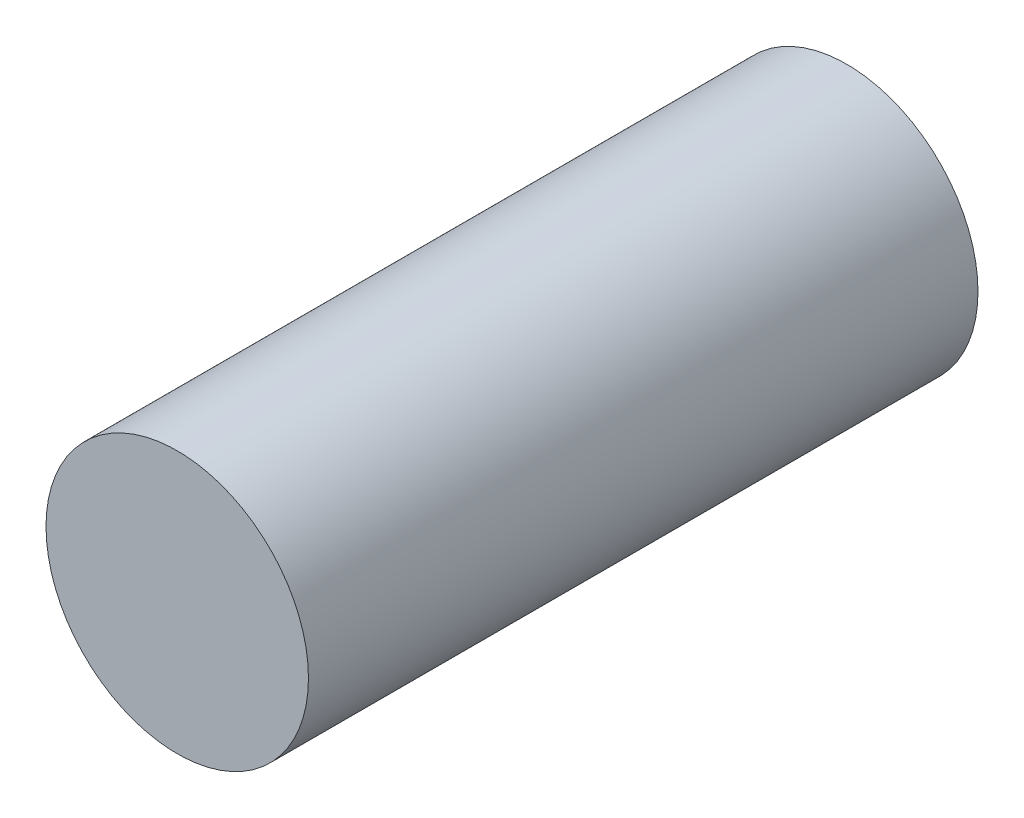
SolidWorks part; units mm, degrees
material "Delrin 2700 NC010, Low Viscosity Acetal Copolymer (SS)"
ref_plane "Front Plane" through (0, 0, 0) normal (0, 0, 1) x (1, 0, 0)
ref_plane "Top Plane" through (0, 0, 0) normal (0, 1, 0) x (1, 0, 0)
ref_plane "Right Plane" through (0, 0, 0) normal (1, 0, 0) x (0, 0, -1)
sketch "Sketch1" plane through (0, 0, 0) normal (0, 0, 1) x (1, 0, 0)
  circle A0 centre (0, 0) radius 1.2446
  dimension "D1" = 2.4892
extrude "Boss-Extrude1" add sketch "Sketch1" along normal blind 6.35
